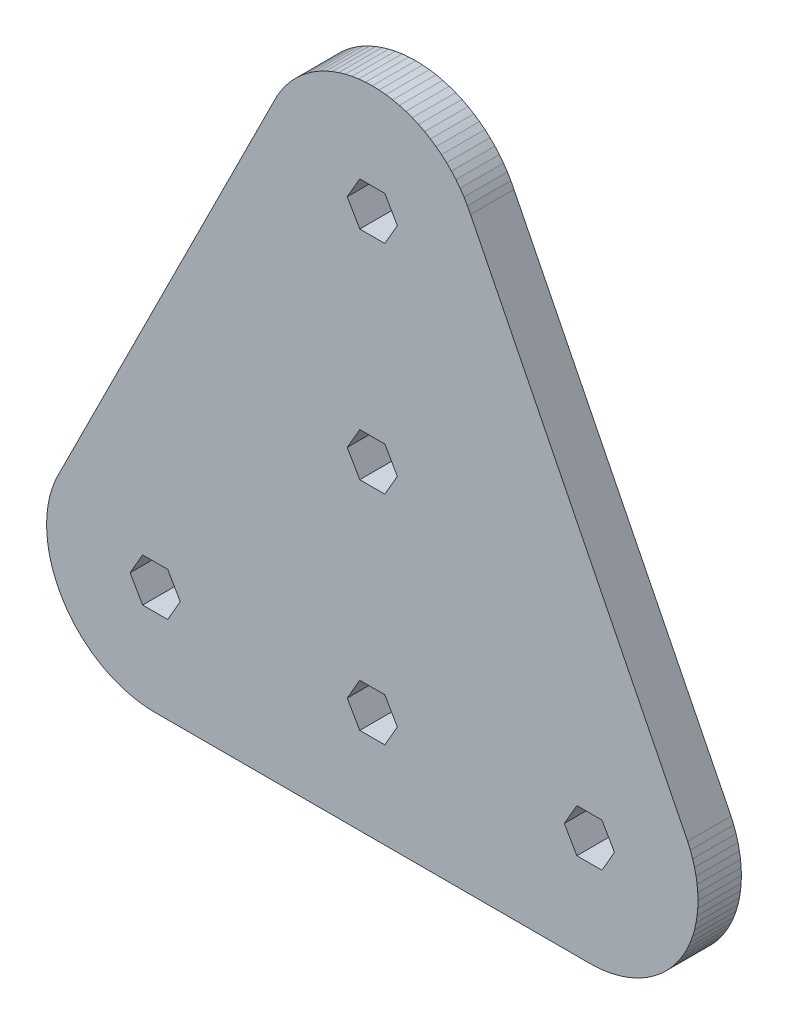
SolidWorks part; units mm, degrees
ref_plane "Front Plane" through (0, 0, 0) normal (0, 0, 1) x (1, 0, 0)
ref_plane "Top Plane" through (0, 0, 0) normal (0, 1, 0) x (1, 0, 0)
ref_plane "Right Plane" through (0, 0, 0) normal (1, 0, 0) x (0, 0, -1)
ref_plane "Plane4" through (0, 0, 3) normal (0, 0, 1) x (1, 0, 0)
sketch "Sketch1" plane through (0, 0, 3) normal (0, 0, 1) x (1, 0, 0)
  line L0 (22.3672, -1.4054) -> (22.4409, -0.94)
  line L1 (22.4409, -0.94) -> (22.4852, -0.4709)
  line L2 (22.4852, -0.4709) -> (22.5, 0)
  line L3 (22.5, 0) -> (22.4852, 0.4709)
  line L4 (22.4852, 0.4709) -> (22.4409, 0.94)
  line L5 (22.4409, 0.94) -> (22.3672, 1.4054)
  line L6 (22.3672, 1.4054) -> (22.2644, 1.8652)
  line L7 (22.2644, 1.8652) -> (22.1329, 2.3176)
  line L8 (22.1329, 2.3176) -> (21.9733, 2.7609)
  line L9 (21.9733, 2.7609) -> (21.7862, 3.1933)
  line L10 (21.7862, 3.1933) -> (6.7862, 33.1933)
  line L11 (6.7862, 33.1933) -> (6.5723, 33.6132)
  line L12 (6.5723, 33.6132) -> (6.3325, 34.0187)
  line L13 (6.3325, 34.0187) -> (6.0676, 34.4084)
  line L14 (6.0676, 34.4084) -> (5.7789, 34.7807)
  line L15 (5.7789, 34.7807) -> (5.4673, 35.1341)
  line L16 (5.4673, 35.1341) -> (5.1341, 35.4673)
  line L17 (5.1341, 35.4673) -> (4.7807, 35.7788)
  line L18 (4.7807, 35.7788) -> (4.4084, 36.0676)
  line L19 (4.4084, 36.0676) -> (4.0187, 36.3325)
  line L20 (4.0187, 36.3325) -> (3.6132, 36.5723)
  line L21 (3.6132, 36.5723) -> (3.1933, 36.7862)
  line L22 (3.1933, 36.7862) -> (2.7609, 36.9733)
  line L23 (2.7609, 36.9733) -> (2.3176, 37.1329)
  line L24 (2.3176, 37.1329) -> (1.8652, 37.2644)
  line L25 (1.8652, 37.2644) -> (1.4054, 37.3672)
  line L26 (1.4054, 37.3672) -> (0.94, 37.4409)
  line L27 (0.94, 37.4409) -> (0.4709, 37.4852)
  line L28 (0.4709, 37.4852) -> (0, 37.5)
  line L29 (0, 37.5) -> (-0.4709, 37.4852)
  line L30 (-0.4709, 37.4852) -> (-0.94, 37.4409)
  line L31 (-0.94, 37.4409) -> (-1.4054, 37.3672)
  line L32 (-1.4054, 37.3672) -> (-1.8652, 37.2644)
  line L33 (-1.8652, 37.2644) -> (-2.3176, 37.1329)
  line L34 (-2.3176, 37.1329) -> (-2.7609, 36.9733)
  line L35 (-2.7609, 36.9733) -> (-3.1933, 36.7862)
  line L36 (-3.1933, 36.7862) -> (-3.6132, 36.5723)
  line L37 (-3.6132, 36.5723) -> (-4.0187, 36.3325)
  line L38 (-4.0187, 36.3325) -> (-4.4084, 36.0676)
  line L39 (-4.4084, 36.0676) -> (-4.7807, 35.7788)
  line L40 (-4.7807, 35.7788) -> (-5.1341, 35.4673)
  line L41 (-5.1341, 35.4673) -> (-5.4673, 35.1341)
  line L42 (-5.4673, 35.1341) -> (-5.7789, 34.7807)
  line L43 (-5.7789, 34.7807) -> (-6.0676, 34.4084)
  line L44 (-6.0676, 34.4084) -> (-6.3325, 34.0187)
  line L45 (-6.3325, 34.0187) -> (-6.5723, 33.6132)
  line L46 (-6.5723, 33.6132) -> (-6.7862, 33.1933)
  line L47 (-6.7862, 33.1933) -> (-21.7862, 3.1933)
  line L48 (-21.7862, 3.1933) -> (-21.9733, 2.7609)
  line L49 (-21.9733, 2.7609) -> (-22.1329, 2.3176)
  line L50 (-22.1329, 2.3176) -> (-22.2644, 1.8652)
  line L51 (-22.2644, 1.8652) -> (-22.3672, 1.4054)
  line L52 (-22.3672, 1.4054) -> (-22.4409, 0.94)
  line L53 (-22.4409, 0.94) -> (-22.4852, 0.4709)
  line L54 (-22.4852, 0.4709) -> (-22.5, 0)
  line L55 (-22.5, 0) -> (-22.4852, -0.4709)
  line L56 (-22.4852, -0.4709) -> (-22.4409, -0.94)
  line L57 (-22.4409, -0.94) -> (-22.3672, -1.4054)
  line L58 (-22.3672, -1.4054) -> (-22.2644, -1.8652)
  line L59 (-22.2644, -1.8652) -> (-22.1329, -2.3176)
  line L60 (-22.1329, -2.3176) -> (-21.9733, -2.7609)
  line L61 (-21.9733, -2.7609) -> (-21.7862, -3.1933)
  line L62 (-21.7862, -3.1933) -> (-21.5723, -3.6132)
  line L63 (-21.5723, -3.6132) -> (-21.3325, -4.0187)
  line L64 (-21.3325, -4.0187) -> (-21.0676, -4.4084)
  line L65 (-21.0676, -4.4084) -> (-20.7788, -4.7807)
  line L66 (-20.7788, -4.7807) -> (-20.4673, -5.1341)
  line L67 (-20.4673, -5.1341) -> (-20.1341, -5.4673)
  line L68 (-20.1341, -5.4673) -> (-19.7807, -5.7789)
  line L69 (-19.7807, -5.7789) -> (-19.4084, -6.0676)
  line L70 (-19.4084, -6.0676) -> (-19.0187, -6.3325)
  line L71 (-19.0187, -6.3325) -> (-18.6132, -6.5723)
  line L72 (-18.6132, -6.5723) -> (-18.1933, -6.7862)
  line L73 (-18.1933, -6.7862) -> (-17.7609, -6.9733)
  line L74 (-17.7609, -6.9733) -> (-17.3176, -7.1329)
  line L75 (-17.3176, -7.1329) -> (-16.8652, -7.2644)
  line L76 (-16.8652, -7.2644) -> (-16.4054, -7.3671)
  line L77 (-16.4054, -7.3671) -> (-15.94, -7.4409)
  line L78 (-15.94, -7.4409) -> (-15.4709, -7.4852)
  line L79 (-15.4709, -7.4852) -> (-15, -7.5)
  line L80 (-15, -7.5) -> (15, -7.5)
  line L81 (15, -7.5) -> (15.4709, -7.4852)
  line L82 (15.4709, -7.4852) -> (15.94, -7.4409)
  line L83 (15.94, -7.4409) -> (16.4054, -7.3671)
  line L84 (16.4054, -7.3671) -> (16.8652, -7.2644)
  line L85 (16.8652, -7.2644) -> (17.3176, -7.1329)
  line L86 (17.3176, -7.1329) -> (17.7609, -6.9733)
  line L87 (17.7609, -6.9733) -> (18.1933, -6.7862)
  line L88 (18.1933, -6.7862) -> (18.6132, -6.5723)
  line L89 (18.6132, -6.5723) -> (19.0187, -6.3325)
  line L90 (19.0187, -6.3325) -> (19.4084, -6.0676)
  line L91 (19.4084, -6.0676) -> (19.7807, -5.7789)
  line L92 (19.7807, -5.7789) -> (20.1341, -5.4673)
  line L93 (20.1341, -5.4673) -> (20.4673, -5.1341)
  line L94 (20.4673, -5.1341) -> (20.7788, -4.7807)
  line L95 (20.7788, -4.7807) -> (21.0676, -4.4084)
  line L96 (21.0676, -4.4084) -> (21.3325, -4.0187)
  line L97 (21.3325, -4.0187) -> (21.5723, -3.6132)
  line L98 (21.5723, -3.6132) -> (21.7862, -3.1933)
  line L99 (21.7862, -3.1933) -> (21.9733, -2.7609)
  line L100 (21.9733, -2.7609) -> (22.1329, -2.3176)
  line L101 (22.1329, -2.3176) -> (22.2644, -1.8652)
  line L102 (22.2644, -1.8652) -> (22.3672, -1.4054)
  line L103 (0.866, 1.5) -> (1.7321, 0)
  line L104 (1.7321, 0) -> (0.866, -1.5)
  line L105 (0.866, -1.5) -> (-0.866, -1.5)
  line L106 (-0.866, -1.5) -> (-1.7321, 0)
  line L107 (-1.7321, 0) -> (-0.866, 1.5)
  line L108 (-0.866, 1.5) -> (0.866, 1.5)
  line L109 (-0.866, 31.5) -> (0.866, 31.5)
  line L110 (0.866, 31.5) -> (1.7321, 30)
  line L111 (1.7321, 30) -> (0.866, 28.5)
  line L112 (0.866, 28.5) -> (-0.866, 28.5)
  line L113 (-0.866, 28.5) -> (-1.7321, 30)
  line L114 (-1.7321, 30) -> (-0.866, 31.5)
  line L115 (15.866, 1.5) -> (16.7321, 0)
  line L116 (16.7321, 0) -> (15.866, -1.5)
  line L117 (15.866, -1.5) -> (14.134, -1.5)
  line L118 (14.134, -1.5) -> (13.2679, 0)
  line L119 (13.2679, 0) -> (14.134, 1.5)
  line L120 (14.134, 1.5) -> (15.866, 1.5)
  line L121 (0.866, 16.5) -> (1.7321, 15)
  line L122 (1.7321, 15) -> (0.866, 13.5)
  line L123 (0.866, 13.5) -> (-0.866, 13.5)
  line L124 (-0.866, 13.5) -> (-1.7321, 15)
  line L125 (-1.7321, 15) -> (-0.866, 16.5)
  line L126 (-0.866, 16.5) -> (0.866, 16.5)
  line L127 (-14.134, 1.5) -> (-13.2679, 0)
  line L128 (-13.2679, 0) -> (-14.134, -1.5)
  line L129 (-14.134, -1.5) -> (-15.866, -1.5)
  line L130 (-15.866, -1.5) -> (-16.7321, 0)
  line L131 (-16.7321, 0) -> (-15.866, 1.5)
  line L132 (-15.866, 1.5) -> (-14.134, 1.5)
  dimension "D1" = 0.0148
  dimension "D2" = 0.0591
  dimension "D3" = 0.1328
  dimension "D4" = 0.2356
  dimension "D5" = 0.3671
  dimension "D6" = 0.5267
  dimension "D7" = 0.7138
  dimension "D8" = 0.9277
  dimension "D9" = 1.1675
  dimension "D10" = 1.4324
  dimension "D11" = 1.7212
  dimension "D12" = 2.0327
  dimension "D13" = 2.3659
  dimension "D14" = 2.7193
  dimension "D15" = 3.0916
  dimension "D16" = 3.4813
  dimension "D17" = 3.8868
  dimension "D18" = 4.3067
  dimension "D19" = 4.7391
  dimension "D20" = 5.1824
  dimension "D21" = 5.6348
  dimension "D22" = 5.7679
  dimension "D23" = 6.0946
  dimension "D24" = 6.56
  dimension "D25" = 6.634
  dimension "D26" = 7.0291
  dimension "D27" = 7.5
  dimension "D28" = 8.366
  dimension "D29" = 9.2321
  dimension "D30" = 15.7138
  dimension "D31" = 15.9277
  dimension "D32" = 16.1675
  dimension "D33" = 16.4324
  dimension "D34" = 16.7211
  dimension "D35" = 17.0327
  dimension "D36" = 17.3659
  dimension "D37" = 17.7193
  dimension "D38" = 18.0916
  dimension "D39" = 18.4813
  dimension "D40" = 18.8868
  dimension "D41" = 19.3067
  dimension "D42" = 19.7391
  dimension "D43" = 20.1824
  dimension "D44" = 20.6348
  dimension "D45" = 20.7679
  dimension "D46" = 21.0946
  dimension "D47" = 21.56
  dimension "D48" = 21.634
  dimension "D49" = 22.0291
  dimension "D50" = 22.5
  dimension "D51" = 22.9709
  dimension "D52" = 23.366
  dimension "D53" = 23.44
  dimension "D54" = 23.9054
  dimension "D55" = 24.232
  dimension "D56" = 24.3652
  dimension "D57" = 24.8176
  dimension "D58" = 25.2609
  dimension "D59" = 25.6933
  dimension "D60" = 26.1131
  dimension "D61" = 26.5187
  dimension "D62" = 26.9084
  dimension "D63" = 27.2807
  dimension "D64" = 27.6341
  dimension "D65" = 27.9673
  dimension "D66" = 28.2789
  dimension "D67" = 28.5676
  dimension "D68" = 28.8325
  dimension "D69" = 29.0723
  dimension "D70" = 29.2862
  dimension "D71" = 35.7679
  dimension "D72" = 36.634
  dimension "D73" = 37.5
  dimension "D74" = 37.9709
  dimension "D75" = 38.366
  dimension "D76" = 38.44
  dimension "D77" = 38.9054
  dimension "D78" = 39.2321
  dimension "D79" = 39.3652
  dimension "D80" = 39.8176
  dimension "D81" = 40.2609
  dimension "D82" = 40.6933
  dimension "D83" = 41.1132
  dimension "D84" = 41.5187
  dimension "D85" = 41.9084
  dimension "D86" = 42.2807
  dimension "D87" = 42.6341
  dimension "D88" = 42.9673
  dimension "D89" = 43.2788
  dimension "D90" = 43.5676
  dimension "D91" = 43.8325
  dimension "D92" = 44.0723
  dimension "D93" = 44.2862
  dimension "D94" = 44.4733
  dimension "D95" = 44.6329
  dimension "D96" = 44.7644
  dimension "D97" = 44.8672
  dimension "D98" = 44.9409
  dimension "D99" = 44.9852
  dimension "D100" = 45
  dimension "D101" = 0.0148
  dimension "D102" = 0.0591
  dimension "D103" = 0.1329
  dimension "D104" = 0.2356
  dimension "D105" = 0.3671
  dimension "D106" = 0.5267
  dimension "D107" = 0.7138
  dimension "D108" = 0.9277
  dimension "D109" = 1.1675
  dimension "D110" = 1.4324
  dimension "D111" = 1.7211
  dimension "D112" = 2.0327
  dimension "D113" = 2.3659
  dimension "D114" = 2.7193
  dimension "D115" = 3.0916
  dimension "D116" = 3.4813
  dimension "D117" = 3.8868
  dimension "D118" = 4.3067
  dimension "D119" = 4.7391
  dimension "D120" = 5.1824
  dimension "D121" = 5.6348
  dimension "D122" = 6
  dimension "D123" = 6.0946
  dimension "D124" = 6.56
  dimension "D125" = 7.0291
  dimension "D126" = 7.5
  dimension "D127" = 7.9709
  dimension "D128" = 8.44
  dimension "D129" = 8.9054
  dimension "D130" = 9
  dimension "D131" = 9.3652
  dimension "D132" = 9.8176
  dimension "D133" = 10.2609
  dimension "D134" = 10.6933
  dimension "D135" = 21
  dimension "D136" = 22.5
  dimension "D137" = 24
  dimension "D138" = 36
  dimension "D139" = 37.5
  dimension "D140" = 39
  dimension "D141" = 40.6933
  dimension "D142" = 41.1132
  dimension "D143" = 41.5187
  dimension "D144" = 41.9084
  dimension "D145" = 42.2807
  dimension "D146" = 42.6341
  dimension "D147" = 42.9673
  dimension "D148" = 43.2788
  dimension "D149" = 43.5676
  dimension "D150" = 43.8325
  dimension "D151" = 44.0723
  dimension "D152" = 44.2862
  dimension "D153" = 44.4733
  dimension "D154" = 44.6329
  dimension "D155" = 44.7644
  dimension "D156" = 44.8672
  dimension "D157" = 44.9409
  dimension "D158" = 44.9852
  dimension "D159" = 45
extrude "Boss-Extrude1" add sketch "Sketch1" against normal blind 3
